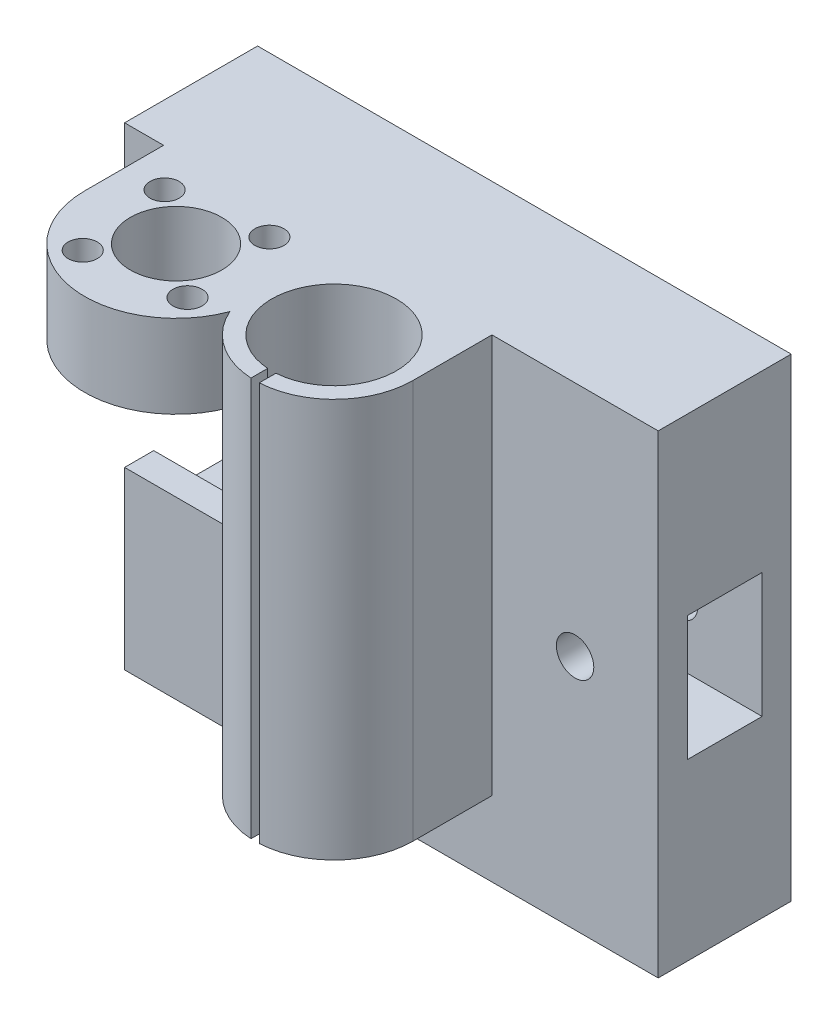
SolidWorks part; units mm, degrees
ref_plane "Front Plane" through (0, 0, 0) normal (0, 0, 1) x (1, 0, 0)
ref_plane "Top Plane" through (0, 0, 0) normal (0, 1, 0) x (1, 0, 0)
ref_plane "Right Plane" through (0, 0, 0) normal (1, 0, 0) x (0, 0, -1)
sketch "Sketch1" plane through (0, 0, 0) normal (0, 1, 0) x (1, 0, 0)
  line L0 (0, 0) -> (64.191, 0)
  line L1 (64.191, 0) -> (64.191, -16)
  line L2 (34.191, -32.9833) -> (34.191, -34.9868)
  line L3 (0, 0) -> (0, -16)
  line L4 (15.691, -25.5) -> (34.691, -25.5) construction
  line L5 (15.691, -25.5) -> (15.691, 0) construction
  line L6 (15.691, -25.5) -> (15.691, -33.5) construction
  line L7 (10.7657, -31.8041) -> (20.6163, -19.1959) construction
  line L8 (9.3869, -20.5747) -> (21.9951, -30.4253) construction
  line L9 (35.191, -32.9833) -> (35.191, -34.9868)
  line L10 (34.691, -25.5) -> (34.691, -32.9833) construction
  line L11 (34.191, -32.9833) -> (35.191, -32.9833) construction
  line L12 (34.191, -34.9868) -> (35.191, -34.9868) construction
  line L13 (64.191, -16) -> (44.191, -16)
  line L14 (44.191, -16) -> (44.191, -25.5)
  line L15 (0, -16) -> (4.691, -16)
  line L16 (4.691, -16) -> (4.691, -25.5)
  circle A0 centre (15.691, -25.5) radius 5.5
  arc A1 (35.191, -32.9833) -> (34.191, -32.9833) centre (34.691, -25.5) ccw
  arc A2 (35.191, -34.9868) -> (44.191, -25.5) centre (34.691, -25.5) ccw
  circle A3 centre (15.691, -25.5) radius 8 construction
  circle A4 centre (10.7657, -31.8041) radius 1.75
  circle A5 centre (9.3869, -20.5747) radius 1.75
  circle A6 centre (20.6163, -19.1959) radius 1.75
  circle A7 centre (21.9951, -30.4253) radius 1.75
  arc A8 (4.691, -25.5) -> (26.0002, -29.3367) centre (15.691, -25.5) ccw
  arc A9 (26.0002, -29.3367) -> (34.191, -34.9868) centre (34.691, -25.5) ccw
  dimension "D1" = 19
  dimension "D2" = 15
  dimension "D3" = 11
  dimension "D5" = 2
  dimension "D6" = 16
  dimension "D7" = 38
  dimension "D8" = 3.5
  dimension "D9" = 22
  dimension "D10" = 1
  dimension "D4" = 25.5
  dimension "D11" = 16
  dimension "D12" = 20
  dimension "D13" = 4.691
extrude "Boss-Extrude1" add sketch "Sketch1" along normal mid plane 57
sketch "Sketch2" plane through (0, 0, 16) normal (0, 0, 1) x (1, 0, 0)
  line L0 (4.691, 28.5) -> (4.691, -28.5) construction
  line L1 (4.691, 18.5) -> (26.0002, 18.5)
  line L2 (4.691, 18.5) -> (4.691, -28.5)
  line L3 (4.691, -28.5) -> (44.191, -28.5)
  line L5 (26.0002, 28.5) -> (4.691, 28.5) construction
  line L6 (26.0002, 18.5) -> (26.0002, -19.5)
  line L7 (26.0002, -19.5) -> (44.191, -19.5)
  line L8 (44.191, 28.5) -> (44.191, -28.5) construction
  line L9 (44.191, -19.5) -> (44.191, -28.5)
  point P1 (14.0443, -19.5)
  point P4 (0, 0)
  dimension "D1" = 10
  dimension "D2" = 9
  dimension "D3" = 21.3092
extrude "Cut-Extrude1" cut sketch "Sketch2" along normal through all
sketch "Sketch3" plane through (0, 0, 0) normal (-1, 0, 0) x (0, 0, 1)
  line L0 (8, 28.5) -> (8, 12.5) construction
  line L1 (3.5, 12.5) -> (12.5, 12.5)
  line L2 (3.5, 12.5) -> (3.5, -12.5)
  line L3 (3.5, -12.5) -> (12.5, -12.5)
  line L4 (12.5, 12.5) -> (12.5, -12.5)
  line L5 (0, 28.5) -> (16, 28.5) construction
  line L6 (0, 0) -> (3.5, 0) construction
  line L7 (0, 28.5) -> (0, -28.5) construction
  line L8 (0, -28.5) -> (16, -28.5) construction
  dimension "D1" = 3.5
  dimension "D2" = 16
  dimension "D3" = 25
extrude "Cut-Extrude2" cut sketch "Sketch3" against normal blind 28
sketch "Sketch4" plane through (0, 0, 0) normal (-1, 0, 0) x (0, 0, 1)
  line L0 (16, 28.5) -> (16, -28.5) construction
  line L1 (0, 7.4) -> (16, 7.4)
  line L2 (0, 7.4) -> (0, -7.4)
  line L3 (0, -7.4) -> (16, -7.4)
  line L4 (16, 7.4) -> (16, -7.4)
  point P4 (0, 0)
  point P9 (8, 7.4)
  dimension "D1" = 14.8
extrude "Cut-Extrude3" cut sketch "Sketch4" against normal up to surface (26.0002 mm away) up to face at (26.0002, -0.5, 22.6683)
hole_wizard "M4 Clearance Hole1" positions "3DSketch1" profile "Sketch5" hole size "M4" standard "ANSI Metric" end condition through all
sketch3d "3DSketch1"
  line L0 (54.191, 0, 16) -> (64.191, 0, 16) construction
  line L6 (64.191, 28.5, 16) -> (64.191, -28.5, 16) construction
  point P0 (54.191, 0, 16)
  dimension "D1" = 10
sketch "Sketch5" plane through (54.191, 0, 16) normal (1, 0, 0) x (0, -1, 0)
  line L0 (0, 0) -> (0, 16)
  line L1 (0, 16) -> (2.25, 16)
  line L2 (2.25, 16) -> (2.25, 0)
  line L5 (2.25, 0) -> (0, 0)
  line L11 (0, -6.35) -> (0, 107.95) construction
  dimension "Thru Hole Dia." = 4.5
  dimension "Thru Hole Depth" = 16
sketch "Sketch6" plane through (0, 0, 0) normal (-1, 0, 0) x (0, 0, 1)
  line L0 (8, -22.5) -> (8, 22.5) construction
  line L1 (8, 22.5) -> (8, 28.5) construction
  line L2 (8, -22.5) -> (8, -28.5) construction
  line L3 (0, -28.5) -> (16, -28.5) construction
  line L4 (0, 28.5) -> (16, 28.5) construction
  circle A0 centre (8, 22.5) radius 4.1
  circle A1 centre (8, -22.5) radius 3.9945
  dimension "D1" = 45
  dimension "D2" = 8.2
extrude "Cut-Extrude4" cut sketch "Sketch6" against normal blind 30 contours A1 | A0
sketch "Sketch7" plane through (28, 0, 0) normal (-1, 0, 0) x (0, 0, 1)
  line L0 (0, 0) -> (3.5, 0) construction
  line L1 (3.5, 7.5) -> (12.5, 7.5)
  line L2 (3.5, 7.5) -> (3.5, -7.5)
  line L3 (3.5, -7.5) -> (12.5, -7.5)
  line L4 (12.5, 7.5) -> (12.5, -7.5)
  line L5 (8, 7.5) -> (8, 12.5) construction
  line L6 (12.5, 12.5) -> (3.5, 12.5) construction
  line L7 (12.5, -12.5) -> (12.5, 12.5) construction
  point P9 (8, 12.5)
  point P12 (0, 0)
  point P13 (0, 0)
  point P14 (12.5, 5.0272)
  dimension "D1" = 15
extrude "Cut-Extrude5" cut sketch "Sketch7" against normal through all
